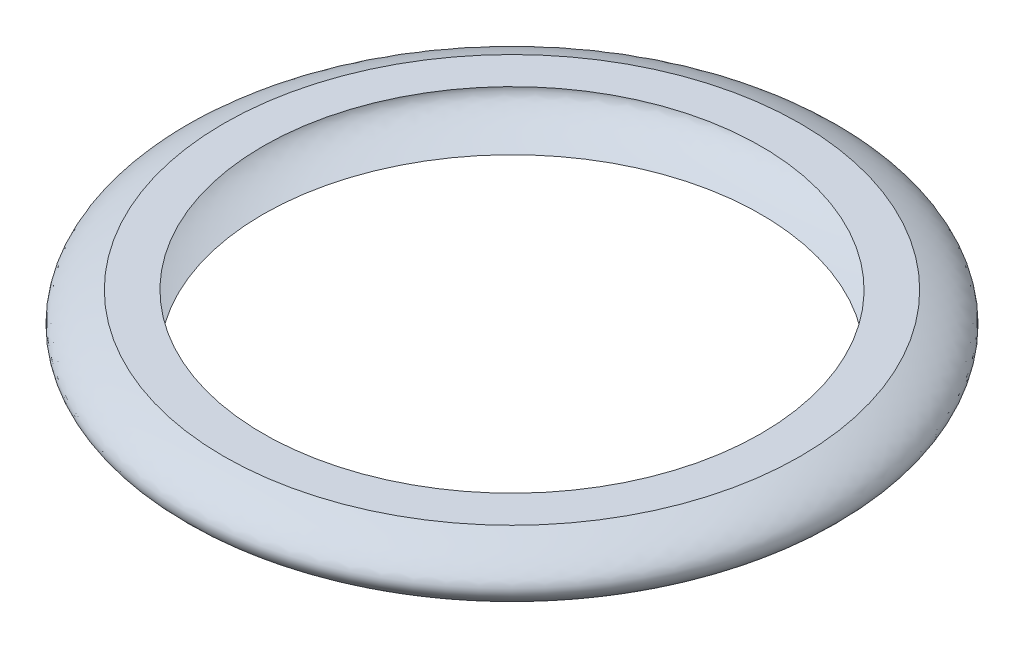
SolidWorks part; units mm, degrees
ref_plane "Front" through (0, 0, 0) normal (0, 0, 1) x (1, 0, 0)
ref_plane "Top" through (0, 0, 0) normal (0, 1, 0) x (1, 0, 0)
ref_plane "Right" through (0, 0, 0) normal (1, 0, 0) x (0, 0, -1)
sketch "Sketch1" plane through (0, 0, 0) normal (0, 1, 0) x (1, 0, 0)
  circle A0 centre (0, 0) radius 31.665
  dimension "D1" = 63.33
sketch "Sketch2" plane through (0, 0, 0) normal (0, 0, 1) x (1, 0, 0)
  line L0 (0, 0) -> (-31.665, 0) construction
  line L1 (31.665, 0) -> (-31.665, 0) construction
  line L2 (0, 3.75) -> (-42.165, 3.75) construction
  line L3 (0, 7.5) -> (-31.665, 7.5) construction
  line L4 (0, 7.5) -> (0, 0) construction
  line L5 (-31.665, 0) -> (-42.165, 3.75) construction
  line L6 (-42.165, 3.75) -> (-31.665, 7.5) construction
  line L7 (-36.665, 0) -> (-47.165, 3.75) construction
  line L8 (-47.165, 3.75) -> (-36.665, 7.5) construction
  line L9 (-31.665, 7.5) -> (-36.665, 7.5)
  line L10 (-31.665, 0) -> (-36.665, 0)
  spline S0 degree 2 poles (-31.665, 0) (-42.165, 3.75) (-31.665, 7.5) knots 0 0 0 1 1 1
  spline S1 degree 2 poles (-36.665, 0) (-47.165, 3.75) (-36.665, 7.5) knots 0 0 0 1 1 1
  dimension "D1" = 31.665
  dimension "D2" = 7.5
  dimension "D3" = 10.5
  dimension "D5" = 5
  dimension "D4" = 2
revolve "Revolve1" add sketch "Sketch2" angle 360 about L4
